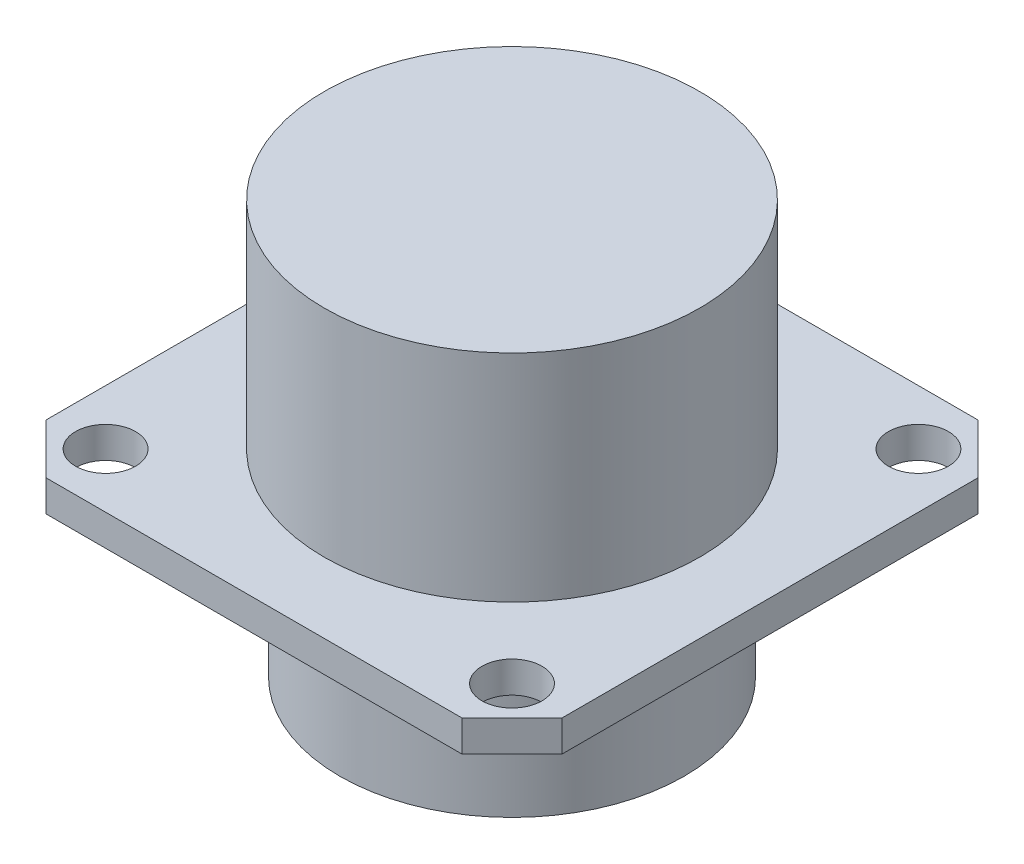
SolidWorks part; units mm, degrees
material "6061-T6 (SS)"
ref_plane "Front Plane" through (0, 0, 0) normal (0, 0, 1) x (1, 0, 0)
ref_plane "Top Plane" through (0, 0, 0) normal (0, 1, 0) x (1, 0, 0)
ref_plane "Right Plane" through (0, 0, 0) normal (1, 0, 0) x (0, 0, -1)
sketch "Sketch1" plane through (0, 0, 0) normal (0, 1, 0) x (1, 0, 0)
  line L1 (-13.0937, 13.0937) -> (13.0937, 13.0937)
  line L2 (-13.0937, 13.0937) -> (-13.0937, -13.0937)
  line L3 (-13.0937, -13.0937) -> (13.0937, -13.0937)
  line L4 (13.0937, 13.0937) -> (13.0937, -13.0937)
  line L5 (-13.0937, 13.0937) -> (13.0937, -13.0937) construction
  line L6 (-13.0937, -13.0937) -> (13.0937, 13.0937) construction
  point P0 (0, 0)
  dimension "D1" = 26.1874
extrude "Boss-Extrude1" add sketch "Sketch1" along normal blind 1.5875
chamfer "Chamfer1" distance 2.54 angle 45 4 edges at (-13.0937, 0.7937, -13.0937) (13.0937, 0.7937, -13.0937) (13.0937, 0.7937, 13.0937) (-13.0937, 0.7937, 13.0937)
sketch "Sketch2" plane through (0, 1.5875, 0) normal (0, 1, 0) x (1, 0, 0)
  line L1 (-10.3124, 10.3124) -> (10.3124, 10.3124) construction
  line L2 (-10.3124, 10.3124) -> (-10.3124, -10.3124) construction
  line L3 (-10.3124, -10.3124) -> (10.3124, -10.3124) construction
  line L4 (10.3124, 10.3124) -> (10.3124, -10.3124) construction
  line L5 (-10.3124, 10.3124) -> (10.3124, -10.3124) construction
  line L6 (-10.3124, -10.3124) -> (10.3124, 10.3124) construction
  circle A0 centre (-10.3124, 10.3124) radius 1.524
  circle A1 centre (10.3124, 10.3124) radius 1.524
  circle A2 centre (10.3124, -10.3124) radius 1.524
  circle A3 centre (-10.3124, -10.3124) radius 1.524
  point P0 (0, 0)
  dimension "D2" = 3.048
  dimension "D1" = 20.6248
extrude "Cut-Extrude1" cut sketch "Sketch2" against normal through all
sketch "Sketch3" plane through (0, 1.5875, 0) normal (0, 1, 0) x (1, 0, 0)
  circle A0 centre (0, 0) radius 9.525
  dimension "D1" = 19.05
extrude "Boss-Extrude2" add sketch "Sketch3" along normal blind 10.9474
sketch "Sketch4" plane through (0, 0, 0) normal (0, -1, 0) x (1, 0, 0)
  circle A0 centre (0, 0) radius 8.7376
  dimension "D1" = 17.4752
extrude "Boss-Extrude3" add sketch "Sketch4" along normal blind 8.4328
